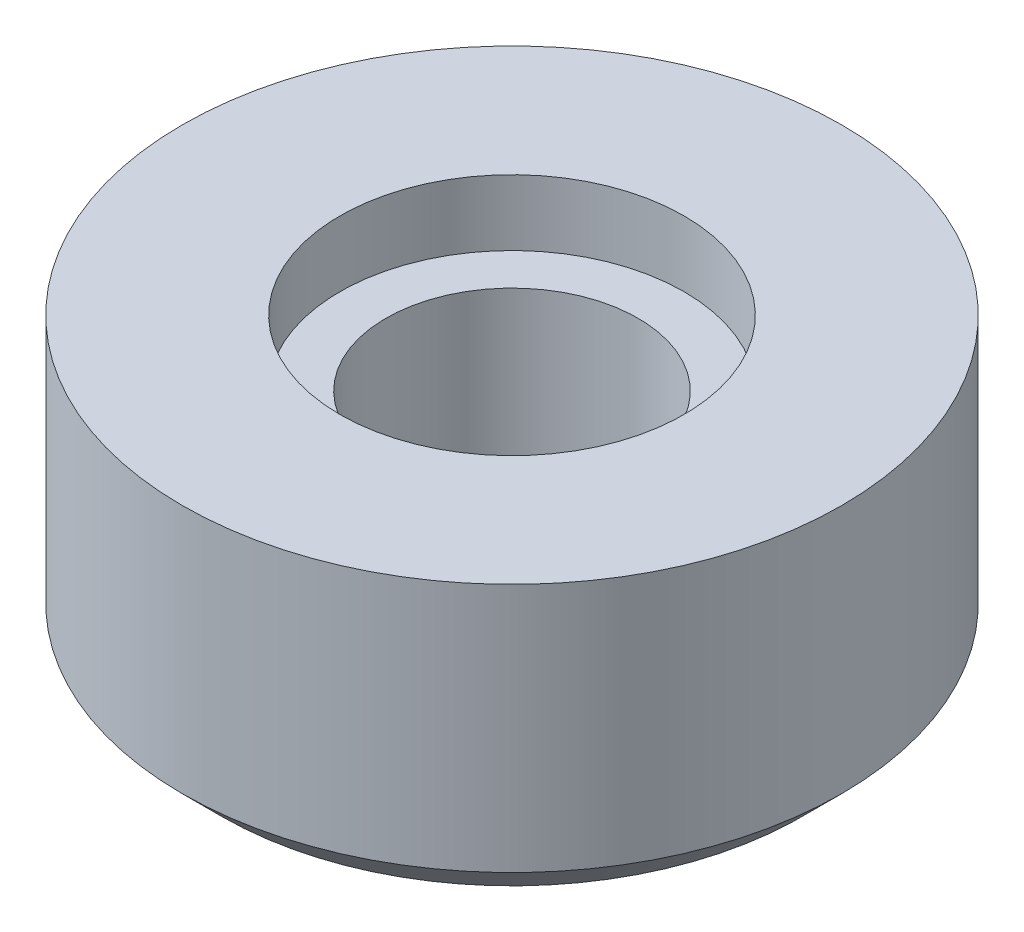
SolidWorks part; units mm, degrees
material "Rubber"
ref_plane "Front Plane" through (0, 0, 0) normal (0, 0, 1) x (1, 0, 0)
ref_plane "Top Plane" through (0, 0, 0) normal (0, 1, 0) x (1, 0, 0)
ref_plane "Right Plane" through (0, 0, 0) normal (1, 0, 0) x (0, 0, -1)
sketch "Sketch2" plane through (0, 0, 0) normal (0, 0, 1) x (1, 0, 0)
  line L0 (4.8, 0) -> (11.05, 0)
  line L1 (11.05, 0) -> (12.55, 1.5)
  line L2 (12.55, 1.5) -> (12.55, 11)
  line L3 (12.55, 11) -> (6.55, 11)
  line L4 (6.55, 11) -> (6.55, 8.5)
  line L5 (6.55, 8.5) -> (4.8, 8.5)
  line L6 (4.8, 8.5) -> (4.8, 0)
  line L7 (0, 14.455) -> (0, -6.5746) construction
  dimension "D1" = 4.8
  dimension "D2" = 9.5
  dimension "D3" = 6
  dimension "D4" = 1.5
  dimension "D5" = 7.75
  dimension "D6" = 2.5
  dimension "D7" = 1.5
revolve "Revolve1" add sketch "Sketch2" angle 360 about L7
